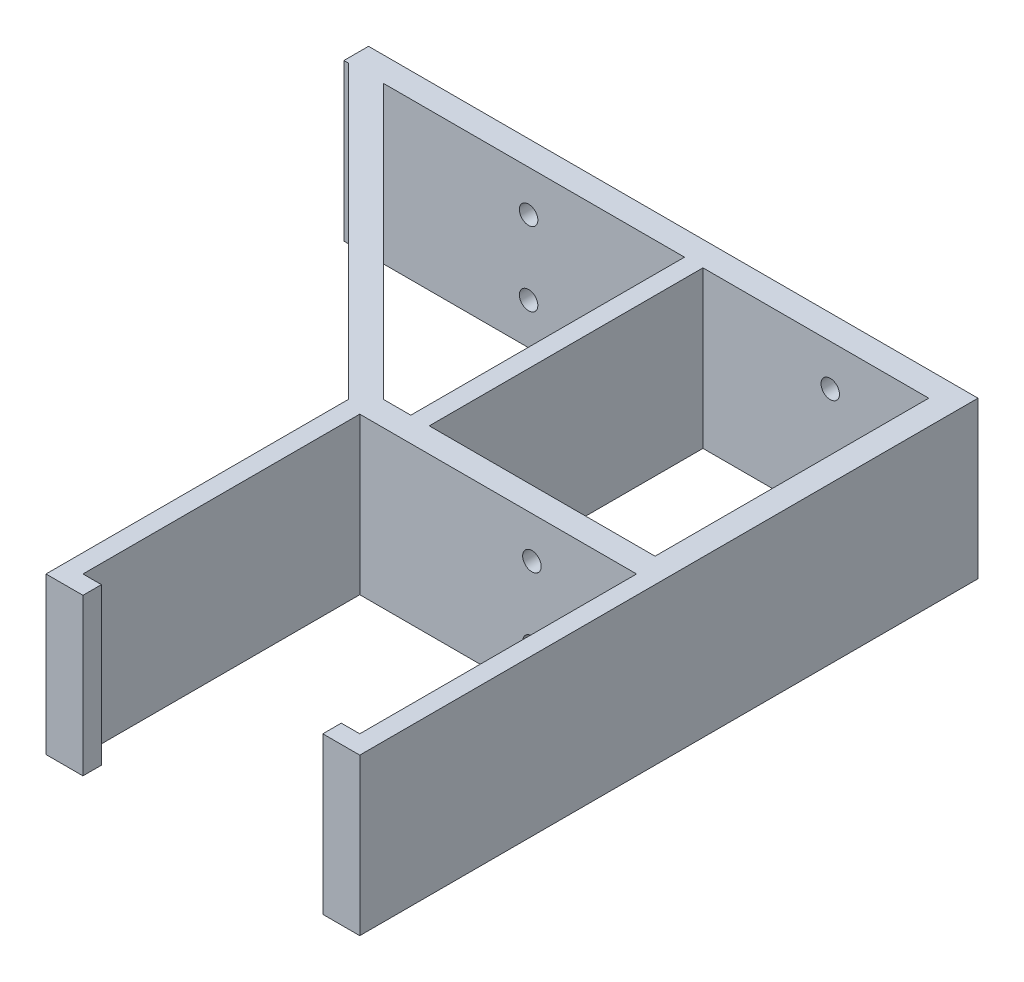
SolidWorks part; units mm, degrees
ref_plane "Front Plane" through (0, 0, 0) normal (0, 0, 1) x (1, 0, 0)
ref_plane "Top Plane" through (0, 0, 0) normal (0, 1, 0) x (1, 0, 0)
ref_plane "Right Plane" through (0, 0, 0) normal (1, 0, 0) x (0, 0, -1)
sketch "Sketch1" plane through (0, 0, 0) normal (0, 1, 0) x (1, 0, 0)
  line L0 (-21.8291, -2.6056) -> (29.1289, -2.6056) construction
  line L1 (-21.8291, -28.5846) -> (29.1289, -28.5846)
  line L2 (-21.8291, -28.5846) -> (-21.8291, 23.3734)
  line L3 (-21.8291, 23.3734) -> (29.1289, 23.3734)
  line L4 (29.1289, -28.5846) -> (29.1289, 23.3734)
  line L5 (-18.8291, 19.3734) -> (26.1289, 19.3734)
  line L6 (-18.8291, 19.3734) -> (-18.8291, -25.5846)
  line L7 (-18.8291, -25.5846) -> (26.1289, -25.5846)
  line L8 (26.1289, 19.3734) -> (26.1289, -25.5846)
  line L9 (3.6499, 23.3734) -> (3.6499, -28.5846) construction
  line L10 (-21.8291, 23.3734) -> (-35.1469, 36.6912) construction
  line L11 (-65.1029, 70.2044) -> (72.4026, 70.2044) construction
  line L12 (3.6499, -2.6056) -> (29.1289, 23.3734) construction
  line L13 (-18.8291, 19.3734) -> (-14.5388, 23.3734) construction
  line L14 (-14.5388, 23.3734) -> (-21.8291, 16.5764) construction
  line L15 (26.1289, 19.3734) -> (22.3995, 23.3734) construction
  line L16 (22.3995, 23.3734) -> (29.1289, 16.1557) construction
  line L21 (3.6499, -2.6056) -> (3.6499, 70.2044) construction
  line L34 (-35.1469, 36.6912) -> (-76.4646, 78.0089) construction
  line L35 (-15.8291, -28.5846) -> (23.1289, -28.5846)
  line L36 (-15.8291, -28.5846) -> (-15.8291, -25.5846)
  line L37 (-15.8291, -25.5846) -> (23.1289, -25.5846)
  line L38 (23.1289, -28.5846) -> (23.1289, -25.5846)
  line L39 (29.1289, 23.3734) -> (25.1289, 23.3734)
  line L40 (-21.8291, 23.3734) -> (-20.4149, 21.9592) construction
  line L42 (-20.4149, 21.9592) -> (-19.0007, 23.3734) construction
  line L43 (-19.0007, 23.3734) -> (-21.8291, 20.545) construction
  line L45 (-21.8291, 20.545) -> (-19.0007, 23.3734)
  line L46 (-21.8291, 20.545) -> (-70.2681, 68.984)
  line L47 (-19.0007, 23.3734) -> (-67.4397, 71.8124)
  line L48 (-70.2681, 68.984) -> (-67.4397, 71.8124)
  line L49 (29.1289, 23.3734) -> (29.1289, 71.8234)
  line L50 (25.1289, 23.3734) -> (25.1289, 71.8234)
  line L51 (29.1289, 71.8234) -> (25.1289, 71.8234)
  line L52 (25.1289, 67.8234) -> (25.1289, 71.8234)
  line L53 (25.1289, 67.8234) -> (-69.8572, 67.8234)
  line L54 (25.1289, 71.8234) -> (-69.8572, 71.8234)
  line L55 (-69.8572, 67.8234) -> (-69.8572, 71.8234)
  line L56 (-14.5388, 23.3734) -> (-11.5388, 23.3734)
  line L57 (-14.5388, 23.3734) -> (-14.5388, 67.8234)
  line L58 (-11.5388, 23.3734) -> (-11.5388, 67.8234)
  line L59 (-14.5388, 67.8234) -> (-11.5388, 67.8234)
  dimension "D3" = 3
  dimension "D4" = 3
  dimension "D5" = 4
  dimension "D6" = 3
  dimension "D13" = 6
  dimension "D14" = 6
  dimension "D2" = 44.958
  dimension "D17" = 44.958
  dimension "D8" = 4
  dimension "D7" = 4
  dimension "D9" = 44.45
  dimension "D10" = 3
  dimension "D11" = 0
extrude "Boss-Extrude1" add sketch "Sketch1" along normal blind 25.4 contours L3 L58 L53 L57 | L49 L51 L50 L3 | L55 L48 L47 L53 L50 L54 | L55 L46 L53 L47 L48 | L55 L53 L46 | L47 L53 L46 L2 L3 | L45 L2 L1 L36 L7 L6 L5 L8 L38 L4 L3 | L2 L45 L3
sketch "Sketch10" plane through (0, 0, -71.8234) normal (0, 0, -1) x (-1, 0, 0)
  line L0 (69.8572, 12.7) -> (-29.1289, 12.7) construction
  line L1 (69.8572, 25.4) -> (69.8572, 0) construction
  line L2 (-29.1289, 25.4) -> (-29.1289, 0) construction
  circle A0 centre (39.8572, 6.7) radius 1.5
  circle A1 centre (39.8572, 18.7) radius 1.5
  circle A2 centre (-9.1289, 6.7) radius 1.5
  circle A3 centre (-9.1289, 18.7) radius 1.5
  dimension "D1" = 3
  dimension "D4" = 6
  dimension "D2" = 30
  dimension "D3" = 6
  dimension "D5" = 20
extrude "Cut-Extrude1" cut sketch "Sketch10" against normal through all
equation "\"D14@Sketch1\"=\"D13@Sketch1\""
